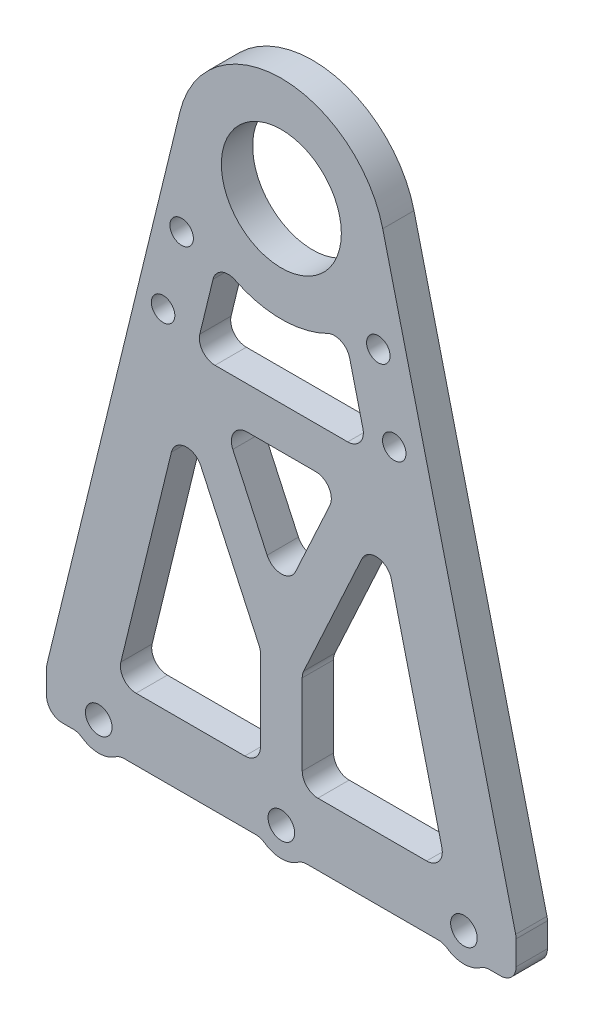
SolidWorks part; units mm, degrees
material "Thornel Mat VMA"
ref_plane "前视基准面" through (0, 0, 0) normal (0, 0, 1) x (1, 0, 0)
ref_plane "上视基准面" through (0, 0, 0) normal (0, 1, 0) x (1, 0, 0)
ref_plane "右视基准面" through (0, 0, 0) normal (1, 0, 0) x (0, 0, -1)
sketch "草图1" plane through (0, 0, 0) normal (0, 0, 1) x (1, 0, 0)
  line L0 (-45, 0) -> (-19.4294, 104.7432)
  line L1 (-45, 0) -> (45, 0)
  line L13 (19.4294, 104.7432) -> (45, 0)
  circle A0 centre (0, 100) radius 20
  circle A5 centre (0, 100) radius 11.5
  point P0 (0, 0)
  dimension "D4" = 40
  dimension "D9" = 23
  dimension "D1" = 100
  dimension "D2" = 90
extrude "凸台-拉伸1" add sketch "草图1" along normal blind 6
sketch "草图5" plane through (0, 0, 6) normal (0, 0, 1) x (1, 0, 0)
  line L1 (-45, 0) -> (45, 0)
  line L2 (-45, 0) -> (-45, -8)
  line L3 (-45, -8) -> (45, -8)
  line L4 (45, 0) -> (45, -8)
  dimension "D1" = 8
extrude "凸台-拉伸2" add sketch "草图5" against normal up to surface (6 mm away) up to face at (11.5, 100, 0)
sketch "草图6" plane through (0, 0, 6) normal (0, 0, 1) x (1, 0, 0)
  circle A0 centre (-22.6679, 70.3828) radius 2.1 construction
  circle A1 centre (21.6433, 69.626) radius 2.1 construction
  circle A2 centre (18.5856, 84.311) radius 2.1 construction
  circle A3 centre (-19.1104, 84.9548) radius 2.1 construction
  circle A4 centre (-22.6679, 70.3828) radius 2.1
  circle A5 centre (21.6433, 69.626) radius 2.1
  circle A6 centre (18.5856, 84.311) radius 2.1
  circle A7 centre (-19.1104, 84.9548) radius 2.1
extrude "切除-拉伸1" cut sketch "草图6" against normal through all
hole_wizard "M4 六角凹锥坑螺钉的锥形沉头孔1" positions "草图7" profile "草图8" countersink size "M4" standard "ISO"
sketch "草图7" plane through (0, 0, 0) normal (0, 0, -1) x (-1, 0, 0)
  point P0 (22.6679, 70.3828)
  point P3 (19.1104, 84.9548)
  point P6 (-18.5856, 84.311)
  point P9 (-21.6433, 69.626)
sketch "草图8" plane through (-22.6679, 70.3828, 0) normal (1, 0, 0) x (0, 1, 0)
  line L0 (0, 0) -> (0, 12.7519)
  line L1 (0, 12.7519) -> (2.25, 11.4)
  line L2 (2.25, 11.4) -> (2.25, 2.23)
  line L3 (2.25, 2.23) -> (4.48, 0)
  line L5 (4.48, 0) -> (0, 0)
  line L6 (-2.25, 2.23) -> (-4.48, 0) construction
  line L10 (0, 12.7519) -> (-2.25, 11.4) construction
  line L11 (0, -6.35) -> (0, 107.95) construction
  dimension "孔直径" = 4.5
  dimension "孔深度" = 11.4
  dimension "近端锥形沉头孔直径" = 8.96
  dimension "近端锥形沉头孔角度" = 90
  dimension "导头角度" = 118
sketch "草图9" plane through (0, 0, 0) normal (0, 0, -1) x (-1, 0, 0)
  line L0 (-7.7718, 101.8973) -> (-31.6711, 4)
  line L1 (-31.6711, 4) -> (-31.6711, 4)
  line L2 (-31.6711, 4) -> (31.6711, 4)
  line L3 (31.6711, 4) -> (31.6711, 4)
  line L4 (31.6711, 4) -> (7.7718, 101.8973)
  line L5 (-19.4294, 104.7432) -> (-45, 0)
  line L6 (-45, 0) -> (-45, -8)
  line L7 (-45, -8) -> (45, -8)
  line L8 (45, -8) -> (45, 0)
  line L9 (45, 0) -> (19.4294, 104.7432)
  line L10 (-19.4294, 104.7432) -> (-45, 0)
  line L11 (-45, 0) -> (-45, -8)
  line L12 (-45, -8) -> (45, -8)
  line L13 (45, -8) -> (45, 0)
  line L14 (45, 0) -> (19.4294, 104.7432)
  line L15 (-17.5117, 62) -> (17.5117, 62)
  line L16 (-17.5117, 62) -> (0, 24)
  line L17 (0, 24) -> (0, 4)
  line L18 (0, 24) -> (17.5117, 62)
  line L19 (3.6328, 22.3259) -> (21.1446, 60.3259)
  line L20 (-21.1446, 60.3259) -> (-3.6328, 22.3259)
  line L21 (-4, 24) -> (-4, 4)
  line L22 (-3.6328, 25.6741) -> (13.8789, 63.6741)
  line L23 (-13.8789, 63.6741) -> (3.6328, 25.6741)
  line L24 (4, 24) -> (4, 4)
  line L25 (-17.5117, 58) -> (17.5117, 58)
  line L26 (-17.5117, 66) -> (17.5117, 66)
  arc A0 (7.7718, 101.8973) -> (-7.7718, 101.8973) centre (0, 100) ccw
  arc A1 (19.4294, 104.7432) -> (-19.4294, 104.7432) centre (0, 100) ccw
  arc A2 (19.4294, 104.7432) -> (-19.4294, 104.7432) centre (0, 100) ccw
  circle A3 centre (0, 100) radius 20
  dimension "D3" = 70
  dimension "D6" = 20
  dimension "D1" = 0
  dimension "D2" = 12
  dimension "D4" = 4
  dimension "D5" = 4
  dimension "D7" = 4
  dimension "D8" = 4
sketch "草图10" plane through (0, 0, 0) normal (0, 0, -1) x (-1, 0, 0)
  line L0 (-35, -4) -> (35, -4) construction
  line L1 (0, -4) -> (0, -8) construction
  line L2 (-45, -8) -> (45, -8) construction
  circle A0 centre (-35, -4) radius 2.55
  circle A1 centre (0, -4) radius 2.55
  circle A2 centre (35, -4) radius 2.55
  dimension "D3" = 5.1
  dimension "D1" = 4
  dimension "D2" = 70
extrude "切除-拉伸2" cut sketch "草图10" against normal through all
sketch "草图11" plane through (0, 0, 0) normal (0, 0, -1) x (-1, 0, 0)
  line L5 (-19.4294, 104.7432) -> (-45, 0)
  line L6 (-45, 0) -> (-45, -8)
  line L7 (-45, -8) -> (45, -8)
  line L8 (45, -8) -> (45, 0)
  line L9 (45, 0) -> (19.4294, 104.7432)
  line L10 (-19.4294, 104.7432) -> (-45, 0)
  line L11 (-45, 0) -> (-45, -8)
  line L12 (-45, -8) -> (45, -8)
  line L13 (45, -8) -> (45, 0)
  line L14 (45, 0) -> (19.4294, 104.7432)
  circle A0 centre (-35, -4) radius 2.55 construction
  circle A1 centre (-35, -4) radius 2.55
  circle A2 centre (0, -4) radius 2.55 construction
  circle A3 centre (0, -4) radius 2.55
  circle A4 centre (35, -4) radius 2.55 construction
  circle A5 centre (35, -4) radius 2.55
  circle A6 centre (-35, -4) radius 5.55
  circle A7 centre (0, -4) radius 5.55
  circle A8 centre (35, -4) radius 5.55
  arc A10 (19.4294, 104.7432) -> (-19.4294, 104.7432) centre (0, 100) ccw
  arc A11 (19.4294, 104.7432) -> (-19.4294, 104.7432) centre (0, 100) ccw
  dimension "D1" = 3
  dimension "D2" = 0
extrude "凸台-拉伸4" add sketch "草图11" against normal up to surface (6 mm away) contours L12 A6 | L12 A7 | L12 A8
extrude "切除-拉伸3" cut sketch "草图9" against normal through all contours A3 L0 L26 L4 | L25 L23 L22 | L21 L20 L0 L2 | L19 L24 L2 L4
fillet "圆角1" radius 3 25 edges at (12.119, 84.0899, 3) (16.5352, 66, 3) (-16.5352, 66, 3) (-12.119, 84.0899, 3) (11.2641, 58, 3) (0, 33.5572, 3) (-11.2641, 58, 3) (-45, 0, 3) (-45, -8, 3) (-31.1526, -8, 3) (-38.8474, -8, 3) (3.8474, -8, 3) (-3.8474, -8, 3) (38.8474, -8, 3) (31.1526, -8, 3) (45, 0, 3) (4, 23.1227, 3) (19.0369, 55.7524, 3) (31.6711, 4, 3) (4, 4, 3) (-4, 23.1227, 3) (-4, 4, 3) (-31.6711, 4, 3) (-19.0369, 55.7524, 3) (45, -8, 3)
